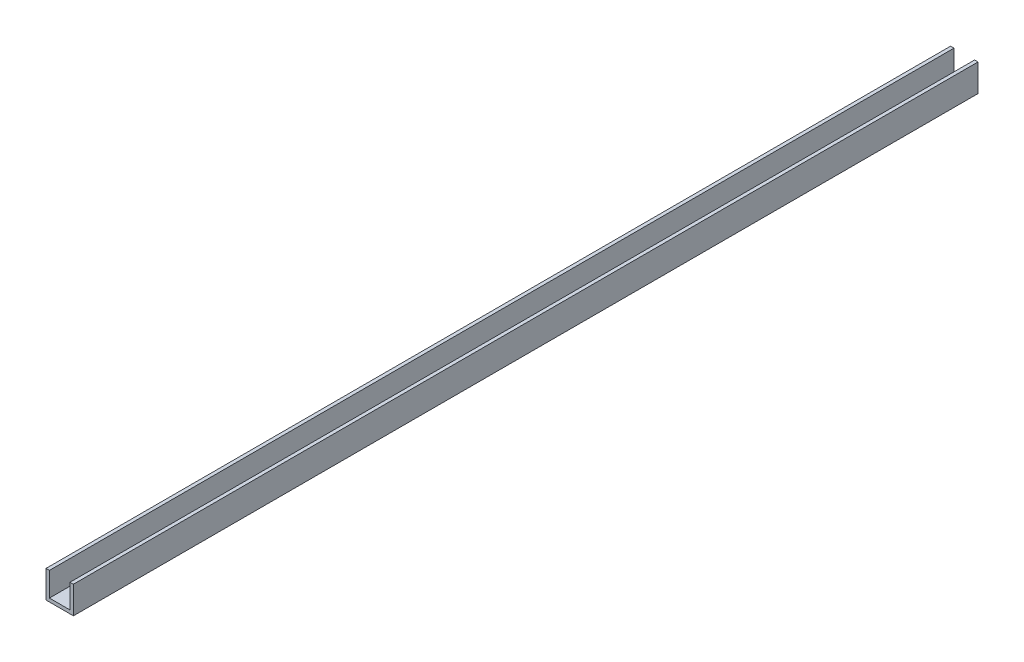
SolidWorks part; units mm, degrees
ref_plane "Front Plane" through (0, 0, 0) normal (0, 0, 1) x (1, 0, 0)
ref_plane "Top Plane" through (0, 0, 0) normal (0, 1, 0) x (1, 0, 0)
ref_plane "Right Plane" through (0, 0, 0) normal (1, 0, 0) x (0, 0, -1)
sketch "Sketch1" plane through (0, 0, 0) normal (0, 0, 1) x (1, 0, 0)
  line L0 (0, 0) -> (0, 25.4)
  line L1 (0, 0) -> (25.4, 0)
  line L2 (25.4, 0) -> (25.4, 25.4)
  dimension "D1" = 25.4
  dimension "D2" = 25.4
  dimension "D3" = 25.4
extrude "Extrude-Thin1" add sketch "Sketch1" along normal blind 838.2 thin
